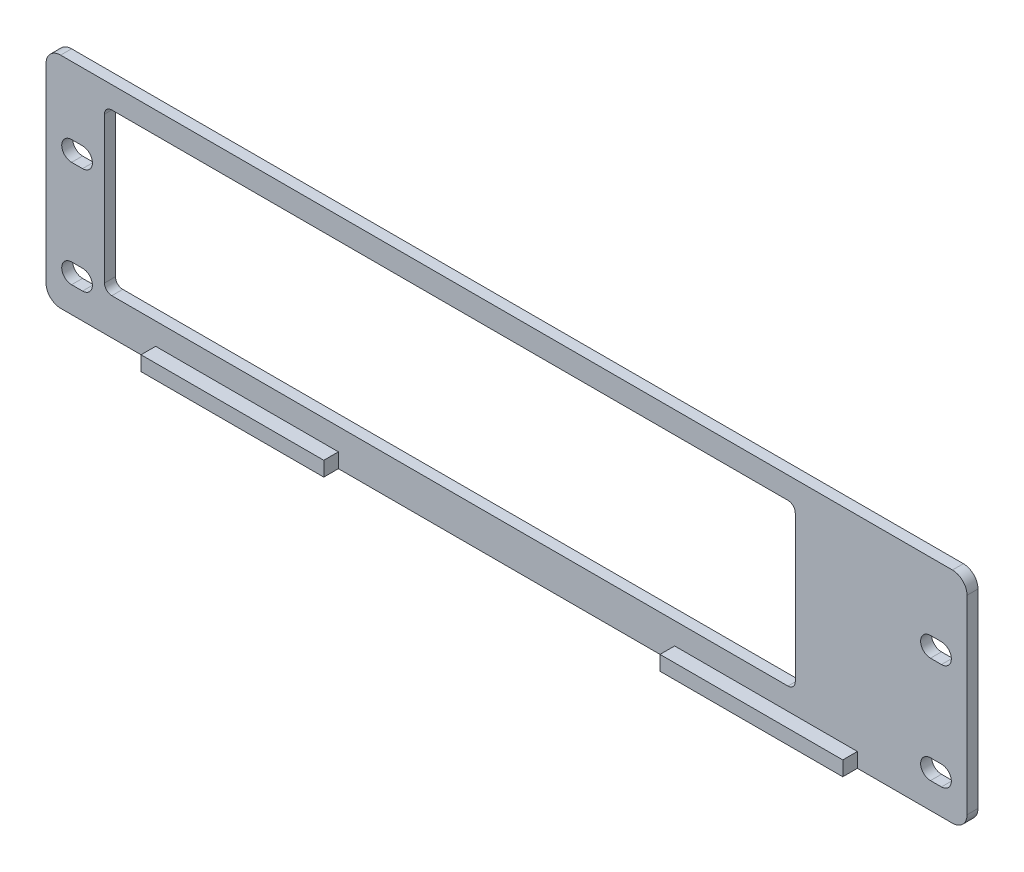
SolidWorks part; units mm, degrees
ref_plane "Front Plane" through (0, 0, 0) normal (0, 0, 1) x (1, 0, 0)
ref_plane "Top Plane" through (0, 0, 0) normal (0, 1, 0) x (1, 0, 0)
ref_plane "Right Plane" through (0, 0, 0) normal (1, 0, 0) x (0, 0, -1)
sketch "Sketch1" plane through (0, 0, 0) normal (0, 0, 1) x (1, 0, 0)
  line L0 (245, 38.8) -> (242, 38.8) construction
  line L1 (0, 0) -> (252, 0)
  line L2 (0, 0) -> (0, 60)
  line L3 (0, 60) -> (252, 60)
  line L4 (252, 0) -> (252, 60)
  line L5 (245, 36.1) -> (242, 36.1)
  line L6 (245, 41.5) -> (242, 41.5)
  line L7 (242, 9.8) -> (245, 9.8) construction
  line L8 (242, 12.5) -> (245, 12.5)
  line L9 (242, 7.1) -> (245, 7.1)
  line L10 (7, 38.8) -> (10, 38.8) construction
  line L11 (7, 41.5) -> (10, 41.5)
  line L12 (7, 36.1) -> (10, 36.1)
  line L13 (7, 9.8) -> (10, 9.8) construction
  line L14 (7, 12.5) -> (10, 12.5)
  line L15 (7, 7.1) -> (10, 7.1)
  arc A4 (245, 36.1) -> (245, 41.5) centre (245, 38.8) ccw
  arc A5 (242, 41.5) -> (242, 36.1) centre (242, 38.8) ccw
  arc A6 (242, 12.5) -> (242, 7.1) centre (242, 9.8) ccw
  arc A7 (245, 7.1) -> (245, 12.5) centre (245, 9.8) ccw
  arc A8 (7, 41.5) -> (7, 36.1) centre (7, 38.8) ccw
  arc A9 (10, 36.1) -> (10, 41.5) centre (10, 38.8) ccw
  arc A10 (7, 12.5) -> (7, 7.1) centre (7, 9.8) ccw
  arc A11 (10, 7.1) -> (10, 12.5) centre (10, 9.8) ccw
  point P7 (8.5, 38.8)
  point P11 (243.5, 9.8)
  point P15 (243.5, 38.8)
  point P26 (8.5, 9.8)
  point P33 (0, 0)
  point P34 (0, 0)
  point P35 (10, 38.8)
  dimension "D5" = 7
  dimension "D7" = 2.7
  dimension "D4" = 2.7
  dimension "D1" = 252
  dimension "D2" = 60
  dimension "D3" = 21.2
  dimension "D6" = 7
  dimension "D8" = 3
  dimension "D9" = 29
  dimension "D10" = 3
extrude "Boss-Extrude1" add sketch "Sketch1" along normal blind 3
sketch "Sketch3" plane through (0, 0, 3) normal (0, 0, 1) x (1, 0, 0)
  line L0 (0, 0) -> (252, 0) construction
  line L1 (30, 0) -> (80, 0)
  line L2 (30, 0) -> (30, 4)
  line L3 (30, 4) -> (80, 4)
  line L4 (80, 0) -> (80, 4)
  line L5 (0, 60) -> (0, 0) construction
  line L6 (222, 0) -> (172, 0)
  line L7 (222, 0) -> (222, 4)
  line L8 (222, 4) -> (172, 4)
  line L9 (172, 0) -> (172, 4)
  line L10 (252, 0) -> (252, 60) construction
  dimension "D1" = 30
  dimension "D2" = 30
  dimension "D3" = 50
  dimension "D4" = 50
  dimension "D5" = 4
  dimension "D6" = 4
extrude "Boss-Extrude3" add sketch "Sketch3" along normal blind 4
sketch "Sketch4" plane through (0, 0, 3) normal (0, 0, 1) x (1, 0, 0)
  line L1 (205, 10) -> (16, 10)
  line L2 (205, 10) -> (205, 54)
  line L3 (205, 54) -> (16, 54)
  line L4 (16, 10) -> (16, 54)
  line L5 (80, 0) -> (172, 0) construction
  line L6 (0, 60) -> (0, 0) construction
  dimension "D1" = 16
  dimension "D2" = 10
  dimension "D3" = 189
  dimension "D4" = 44
extrude "Cut-Extrude1" cut sketch "Sketch4" against normal blind 4
fillet "Fillet1" radius 4 4 edges at (0, 0, 1.5) (252, 0, 1.5) (252, 60, 1.5) (0, 60, 1.5)
fillet "Fillet3" radius 2 4 edges at (205, 54, 1.5) (205, 10, 1.5) (16, 54, 1.5) (16, 10, 1.5)
